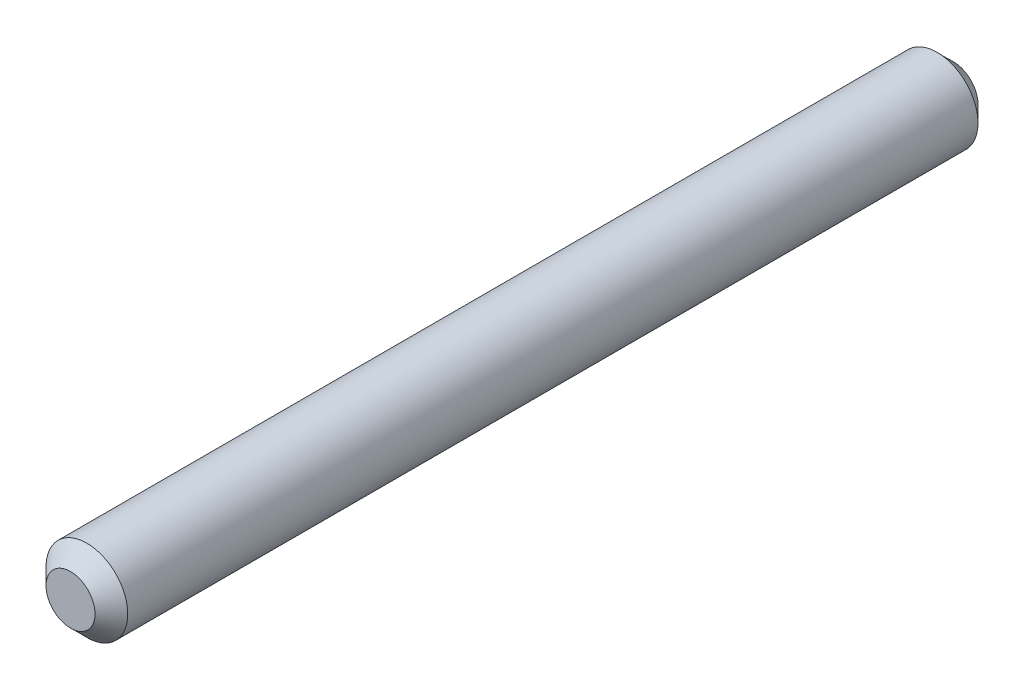
SolidWorks part; units mm, degrees
ref_plane "Front Plane" through (0, 0, 0) normal (0, 0, 1) x (1, 0, 0)
ref_plane "Top Plane" through (0, 0, 0) normal (0, 1, 0) x (1, 0, 0)
ref_plane "Right Plane" through (0, 0, 0) normal (1, 0, 0) x (0, 0, -1)
sketch "Sketch1" plane through (0, 0, 0) normal (0, 0, 1) x (1, 0, 0)
  circle A0 centre (0, 0) radius 2.5
  dimension "D1" = 5
extrude "Boss-Extrude1" add sketch "Sketch1" along normal mid plane 54
chamfer "Chamfer1" distance 1 angle 45 2 edges at (2.5, 0, -27) (2.5, 0, 27)
